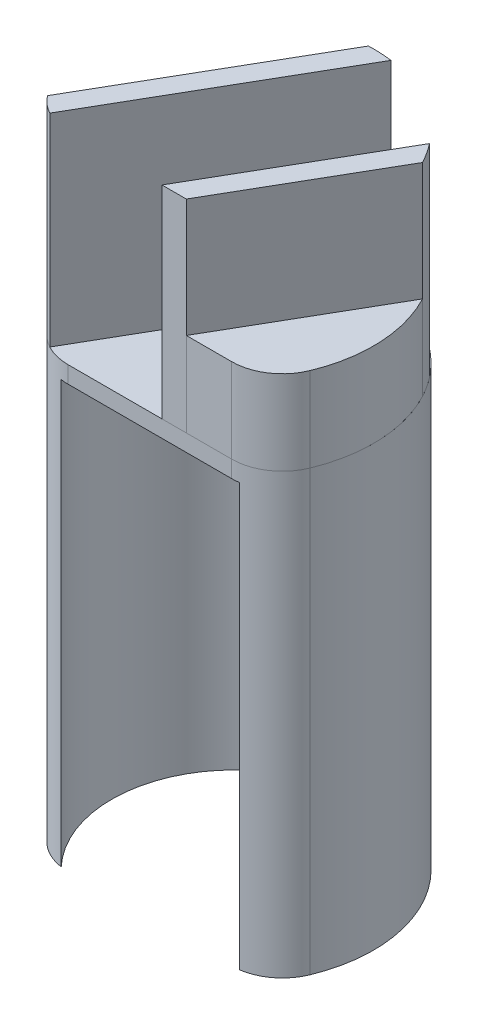
SolidWorks part; units mm, degrees
ref_plane "前视基准面" through (0, 0, 0) normal (0, 0, 1) x (1, 0, 0)
ref_plane "上视基准面" through (0, 0, 0) normal (0, 1, 0) x (1, 0, 0)
ref_plane "右视基准面" through (0, 0, 0) normal (1, 0, 0) x (0, 0, -1)
other "Configuration Table"
sketch "草图1" plane through (0, 0, 0) normal (0, 1, 0) x (1, 0, 0)
  circle A0 centre (0, 0) radius 14.5
  circle A1 centre (0, 0) radius 16.5
  dimension "D1" = 29
  dimension "D2" = 2
extrude "凸台-拉伸1" add sketch "草图1" along normal blind 35
sketch "草图3" plane through (0, 35, 0) normal (0, 1, 0) x (1, 0, 0)
  circle A1 centre (0, 0) radius 16.5
  circle A2 centre (0, 0) radius 16.5
  dimension "D1" = 0
extrude "凸台-拉伸2" add sketch "草图3" along normal blind 2
ref_plane "基准面1" through (0, 0, 10) normal (0, 0, 1) x (1, 0, 0)
sketch "草图4" plane through (0, 0, 10) normal (0, 0, 1) x (1, 0, 0)
  line L1 (-49.9355, 39.7218) -> (28.4145, 39.7218)
  line L2 (-49.9355, 39.7218) -> (-49.9355, -52.0807)
  line L3 (-49.9355, -52.0807) -> (28.4145, -52.0807)
  line L4 (28.4145, 39.7218) -> (28.4145, -52.0807)
extrude "切除-拉伸1" cut sketch "草图4" along normal through all
sketch "草图5" plane through (0, 37, 0) normal (0, 1, 0) x (1, 0, 0)
  circle A0 centre (0, 0) radius 3.75
  dimension "D1" = 7.5
extrude "切除-拉伸2" cut sketch "草图5" against normal up to next
fillet "圆角1" radius 6 2 edges at (13.1244, 18.5, 10) (-13.1244, 18.5, 10)
sketch "草图6" plane through (0, 37, 0) normal (0, 1, 0) x (1, 0, 0)
  line L0 (13.0479, 10.0996) -> (1.4434, -10)
  line L1 (-0.5833, 16.4897) -> (-14.4988, -7.6126)
  line L2 (-24.0688, -10) -> (24.0688, -10) construction
  line L3 (2.2226, 16.3496) -> (-12.5707, -9.2732)
  line L4 (14.5721, 7.7397) -> (4.3301, -10)
  line L5 (-9.7082, -10) -> (9.7082, -10) construction
  line L7 (-9.7082, -10) -> (9.7082, -10)
  line L8 (1.4434, -10) -> (4.3301, -10)
  circle A0 centre (0, 0) radius 6.25 construction
  arc A1 (-15.2558, -6.2857) -> (-9.7082, -10) centre (-9.7082, -4) ccw construction
  arc A2 (15.2558, -6.2857) -> (-15.2558, -6.2857) centre (0, 0) ccw construction
  arc A3 (2.2226, 16.3496) -> (-0.5833, 16.4897) centre (0, 0) ccw
  arc A6 (15.2558, -6.2857) -> (-15.2558, -6.2857) centre (0, 0) ccw
  arc A7 (-15.2558, -6.2857) -> (-9.7082, -10) centre (-9.7082, -4) ccw
  arc A8 (9.7082, -10) -> (15.2558, -6.2857) centre (9.7082, -4) ccw
  arc A9 (14.5721, 7.7397) -> (13.0479, 10.0996) centre (0, 0) ccw
  arc A10 (-14.4988, -7.6126) -> (-12.5707, -9.2732) centre (-9.7082, -4) ccw
  dimension "D1" = 12.5
  dimension "D2" = 60
  dimension "D3" = 2.5
  dimension "D4" = 2.5
  dimension "D5" = 0
extrude "凸台-拉伸3" add sketch "草图6" along normal blind 24 separate body
sketch "草图9" plane through (0, 37, 0) normal (0, 1, 0) x (1, 0, 0)
  line L0 (4.3301, -10) -> (14.5721, 7.7397) construction
  line L1 (-9.7082, -10) -> (9.7082, -10)
  line L2 (4.3301, -10) -> (9.7082, -10)
  line L3 (4.3301, -10) -> (14.5721, 7.7397)
  arc A3 (15.2558, -6.2857) -> (-15.2558, -6.2857) centre (0, 0) ccw
  arc A4 (-15.2558, -6.2857) -> (-9.7082, -10) centre (-9.7082, -4) ccw
  arc A5 (9.7082, -10) -> (15.2558, -6.2857) centre (9.7082, -4) ccw
  arc A6 (15.2558, -6.2857) -> (14.5721, 7.7397) centre (0, 0) ccw
  arc A8 (9.7082, -10) -> (15.2558, -6.2857) centre (9.7082, -4) ccw
  dimension "D1" = 0
extrude "凸台-拉伸7" add sketch "草图9" along normal blind 10 separate body
sketch "草图10" plane through (0, 0, 0) normal (0, -1, 0) x (1, 0, 0)
  arc A4 (-10.5572, 9.9396) -> (10.5572, 9.9396) centre (0, 0) ccw
  arc A6 (-15.2558, 6.2857) -> (15.2558, 6.2857) centre (0, 0) ccw
  arc A10 (-15.2558, 6.2857) -> (15.2558, 6.2857) centre (0, 0) ccw
  arc A13 (-10.5572, 9.9396) -> (10.5572, 9.9396) centre (0, 0) ccw
  arc A16 (-10.5572, 9.9396) -> (-15.2558, 6.2857) centre (-9.7082, 4) ccw
  arc A18 (-10.5572, 9.9396) -> (-15.2558, 6.2857) centre (-9.7082, 4) ccw
  arc A19 (15.2558, 6.2857) -> (10.5572, 9.9396) centre (9.7082, 4) ccw
  arc A20 (15.2558, 6.2857) -> (10.5572, 9.9396) centre (9.7082, 4) ccw
  dimension "D1" = 0
extrude "凸台-拉伸8" add sketch "草图10" along normal blind 15
sketch "草图12" plane through (0, 37, 0) normal (0, 1, 0) x (1, 0, 0)
  line L0 (-11.7068, 12.7233) -> (-15.7072, 5.7943) construction
  line L1 (-0.5833, 16.4897) -> (-14.4988, -7.6126) construction
  line L2 (-14.2894, 8.25) -> (-32.0359, 18.4959) construction
  line L3 (-16.4325, 3.8015) -> (-13.0123, 13.1985)
  line L4 (-13.0123, 13.1985) -> (-10.8657, 12.4172)
  line L5 (-16.4325, 3.8015) -> (-16.0855, 3.6752)
  arc A0 (15.2558, -6.2857) -> (-15.2558, -6.2857) centre (0, 0) ccw construction
  arc A1 (-10.8657, 12.4172) -> (-16.0855, 3.6752) centre (0, 0) ccw
  point P1 (-14.2894, 8.25)
  point P8 (-14.7224, 8.5)
  point P11 (0, 0)
  point P13 (-11.0368, 12.2654)
  dimension "D1" = 10
  dimension "D2" = 10
  dimension "D3" = 0.5
extrude "凸台-拉伸10" add sketch "草图12" against normal blind 40 separate body
